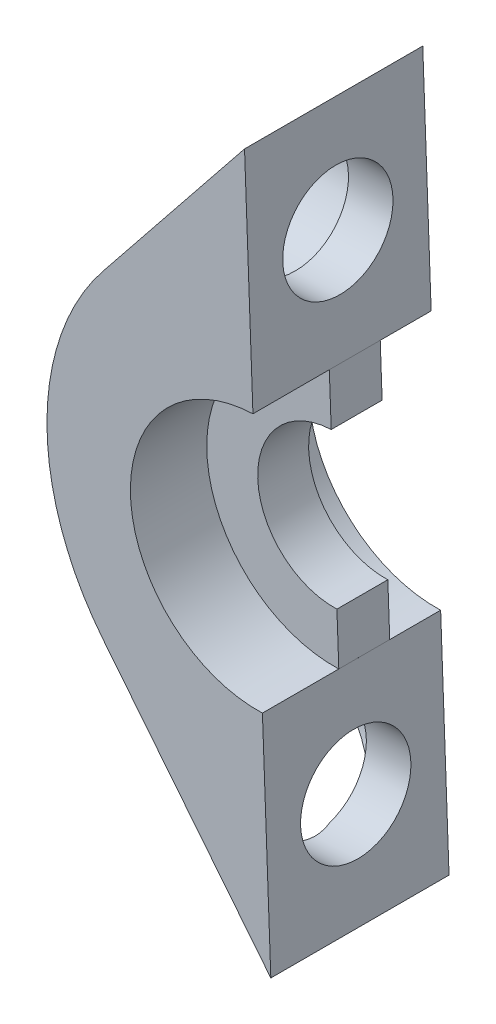
SolidWorks part; units mm, degrees
ref_plane "Front Plane" through (0, 0, 0) normal (0, 0, 1) x (1, 0, 0)
ref_plane "Top Plane" through (0, 0, 0) normal (0, 1, 0) x (1, 0, 0)
ref_plane "Right Plane" through (0, 0, 0) normal (1, 0, 0) x (0, 0, -1)
sketch "Sketch2" plane through (0, 0, 0) normal (0, 0, 1) x (1, 0, 0)
  line L2 (1000, 0) -> (0, 0) construction
  line L3 (1.6665, 18.0743) -> (-7.8044, 6.2523) construction
  line L4 (3.9785, -20.9602) -> (-7.8044, -6.2523) construction
  line L7 (-1.537, -5.6407) -> (-1.2072, -14.4872)
  line L8 (-2.2397, 13.1984) -> (-1.9097, 4.3523)
  line L9 (-2.2397, 13.1984) -> (-7.8044, 6.2523)
  line L10 (-1.2072, -14.4872) -> (-7.8044, -6.2523)
  line L11 (-6.6816, 0) -> (-23.9344, 0) construction
  arc A0 (-7.8044, 6.2523) -> (-7.8044, -6.2523) centre (0, 0) ccw
  arc A1 (-1.9097, 4.3523) -> (-1.537, -5.6407) centre (-1.7233, -0.6442) ccw
  dimension "D1" = 20
  dimension "D3" = 10
  dimension "D4" = 138.595
  dimension "D5" = 1.8398
  dimension "D6" = 13.3871
  dimension "D7" = 14.5374
extrude "Boss-Extrude2" add sketch "Sketch2" along normal blind 7
ref_plane "Plane1" through (0, 0, 4) normal (0, 0, 1) x (1, 0, 0)
sketch "Sketch3" plane through (0, 0, 4) normal (0, 0, 1) x (1, 0, 0)
  line L0 (-1.9098, 4.3523) -> (-1.8352, 2.3537)
  line L1 (-1.6117, -3.6421) -> (-1.5371, -5.6407)
  arc A0 (-1.9098, 4.3523) -> (-1.5371, -5.6407) centre (-1.7233, -0.6442) ccw
  arc A1 (-1.9097, 4.3523) -> (-1.537, -5.6407) centre (-1.7233, -0.6442) ccw construction
  arc A2 (-1.8352, 2.3537) -> (-1.6117, -3.6421) centre (-1.7233, -0.6442) ccw
  dimension "D1" = 2
extrude "Boss-Extrude3" add sketch "Sketch3" against normal blind 2
sketch "Sketch4" plane through (-1.7449, -0.0651, 0) normal (0.9993, 0.0373, 0) x (0, 0, -1)
  line L0 (-7, 4.4205) -> (-7, 13.2728) construction
  line L1 (0, 4.4205) -> (-7, 4.4205) construction
  line L2 (0, 4.4205) -> (0, 13.2728) construction
  line L3 (0, 13.2728) -> (-7, 13.2728) construction
  line L4 (-7, 4.4205) -> (-7, 13.2728) construction
  line L5 (0, 4.4205) -> (-7, 13.2728) construction
  line L6 (0, 13.2728) -> (-7, 4.4205) construction
  line L7 (0, -14.4321) -> (-7, -14.4321) construction
  line L8 (0, -14.4321) -> (0, -5.5795) construction
  line L9 (0, -5.5795) -> (-7, -5.5795) construction
  line L10 (-7, -14.4321) -> (-7, -5.5795) construction
  line L11 (0, -14.4321) -> (-7, -5.5795) construction
  line L12 (0, -5.5795) -> (-7, -14.4321) construction
  line L13 (0, 4.4205) -> (0, 13.2728) construction
  line L14 (-7, 13.2728) -> (0, 13.2728) construction
  line L15 (-7, 4.4205) -> (0, 4.4205) construction
  line L16 (-7, -5.5795) -> (0, -5.5795) construction
  line L17 (-7, -14.4321) -> (0, -14.4321) construction
  circle A0 centre (-3.5, 8.8466) radius 2.165
  circle A1 centre (-3.5, -10.0058) radius 2.165
  point P0 (-3.5, 8.8466)
  point P5 (-3.5, -10.0058)
  dimension "D1" = 4.33
extrude "Cut-Extrude1" cut sketch "Sketch4" against normal up to next
ref_plane "Plane2" through (-5.7421, -0.2142, 0) normal (-0.9993, -0.0373, 0) x (0, 0, 1)
sketch "Sketch6" plane through (-5.7421, -0.2142, 0) normal (-0.9993, -0.0373, 0) x (0, 0, 1)
  circle A0 centre (3.5, -10.0058) radius 3
  circle A1 centre (3.5, 8.8466) radius 3
  dimension "D1" = 6
extrude "Cut-Extrude2" cut sketch "Sketch6" along normal mid plane 4.5
